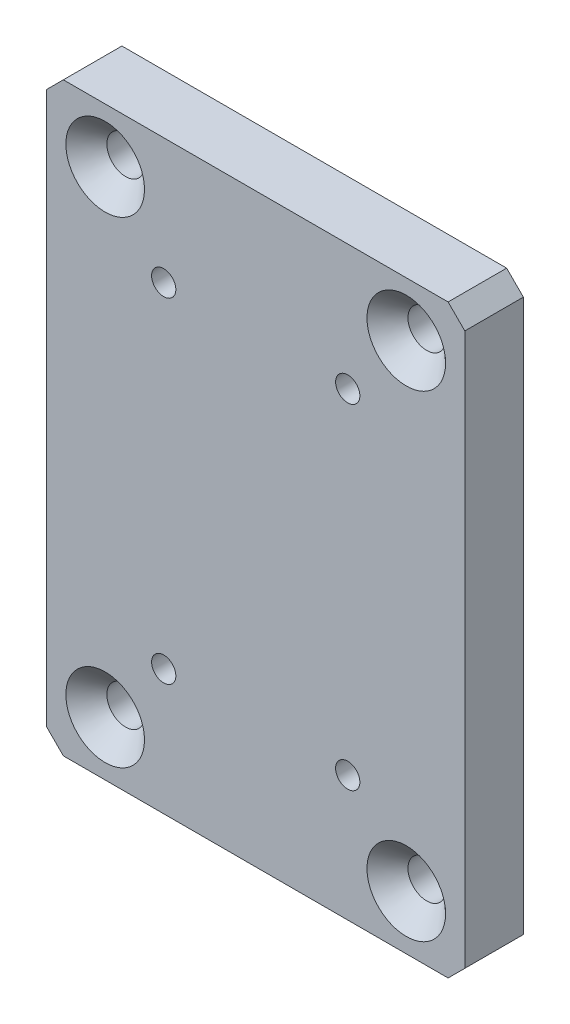
SolidWorks part; units mm, degrees
ref_plane "Front Plane" through (0, 0, 0) normal (0, 0, 1) x (1, 0, 0)
ref_plane "Top Plane" through (0, 0, 0) normal (0, 1, 0) x (1, 0, 0)
ref_plane "Right Plane" through (0, 0, 0) normal (1, 0, 0) x (0, 0, -1)
sketch "Sketch1" plane through (0, 0, 0) normal (0, 0, 1) x (1, 0, 0)
  line L0 (11, 20) -> (-20.0058, 20) construction
  line L1 (-25, 35) -> (25, 35)
  line L2 (-25, 35) -> (-25, -35)
  line L3 (-25, -35) -> (25, -35)
  line L4 (25, 35) -> (25, -35)
  line L5 (-16.9008, 0) -> (15.2337, 0) construction
  line L6 (0, 25.034) -> (0, -16.3715) construction
  circle A0 centre (11, 20) radius 1.35
  circle A1 centre (-11, 20) radius 1.35
  circle A2 centre (-11, -20) radius 1.35
  circle A3 centre (11, -20) radius 1.35
  circle A4 centre (18, 28.5) radius 1.5
  circle A5 centre (-18, 28.5) radius 1.5
  circle A6 centre (-18, -28.5) radius 1.5
  circle A7 centre (18, -28.5) radius 1.5
  point P4 (-25, 0)
  point P5 (25, 0)
  dimension "D4" = 2.7
  dimension "D5" = 22
  dimension "D8" = 3
  dimension "D1" = 70
  dimension "D2" = 50
  dimension "D3" = 25
  dimension "D6" = 14
  dimension "D7" = 40
  dimension "D9" = 7
  dimension "D10" = 6.5
extrude "Boss-Extrude1" add sketch "Sketch1" along normal blind 7
fillet "Chamfer1" radius 2 1 edges at (-25, 35, 3.5) profile chamfer
chamfer "Chamfer2" distance 2 angle 45 1 edges at (-25, -35, 3.5)
chamfer "Chamfer3" distance 2 angle 45 1 edges at (25, -35, 3.5)
chamfer "Chamfer4" distance 2 angle 45 1 edges at (25, 35, 3.5)
hole_wizard "CSK for M4 Countersunk Flat Head Screw1" positions "Sketch5" profile "Sketch6" countersink size "M4" standard "ISO" end condition up to next
sketch "Sketch5" plane through (0, 0, 7) normal (0, 0, 1) x (1, 0, 0)
  point P0 (18, 28.5)
  point P3 (18, -28.5)
  point P6 (-18, -28.5)
  point P9 (-18, 28.5)
sketch "Sketch6" plane through (18, 28.5, 7) normal (1, 0, 0) x (0, -1, 0)
  line L0 (0, 0) -> (0, 7)
  line L1 (0, 7) -> (2.25, 7)
  line L2 (2.25, 7) -> (2.25, 2.45)
  line L3 (2.25, 2.45) -> (4.7, 0)
  line L5 (4.7, 0) -> (0, 0)
  line L6 (-2.25, 2.45) -> (-4.7, 0) construction
  line L11 (0, -6.35) -> (0, 107.95) construction
  dimension "Thru Hole Dia." = 4.5
  dimension "Thru Hole Depth" = 7
  dimension "Near C'Sink Dia." = 9.4
  dimension "Near C'Sink Angle" = 90
hole_wizard "CBORE for M2.5 Hex Socket Head Cap Screw1" positions "Sketch7" profile "Sketch8" counterbore size "M2.5" standard "ISO" end condition through all
sketch "Sketch7" plane through (0, 0, 0) normal (0, 0, -1) x (-1, 0, 0)
  point P0 (11, 20)
  point P3 (-11, 20)
  point P6 (-11, -20)
  point P9 (11, -20)
sketch "Sketch8" plane through (-11, 20, 0) normal (1, 0, 0) x (0, 1, 0)
  line L0 (0, 0) -> (0, 7)
  line L1 (0, 7) -> (1.45, 7)
  line L3 (1.45, 7) -> (1.45, 2.9)
  line L4 (1.45, 2.9) -> (2.75, 2.9)
  line L5 (2.75, 2.9) -> (2.75, 0)
  line L7 (2.75, 0) -> (0, 0)
  line L11 (0, -6.35) -> (0, 107.95) construction
  dimension "Thru Hole Dia." = 2.9
  dimension "Thru Hole Depth" = 7
  dimension "C'Bore Dia." = 5.5
  dimension "C'Bore Depth" = 2.9
